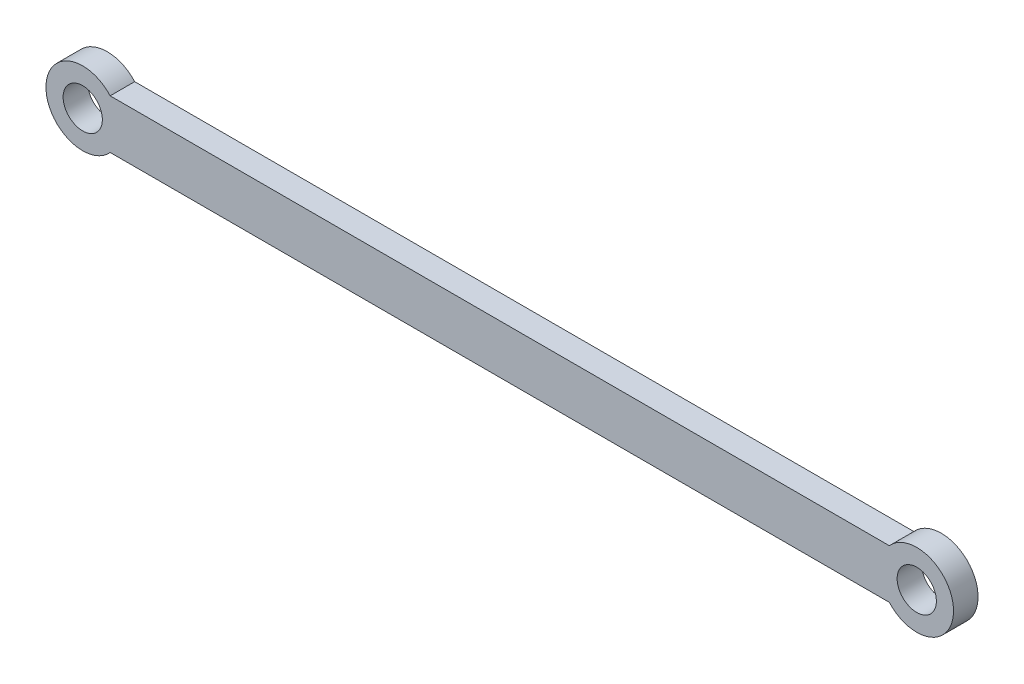
SolidWorks part; units mm, degrees
ref_plane "Piano frontale" through (0, 0, 0) normal (0, 0, 1) x (1, 0, 0)
ref_plane "Piano superiore" through (0, 0, 0) normal (0, 1, 0) x (1, 0, 0)
ref_plane "Piano destro" through (0, 0, 0) normal (1, 0, 0) x (0, 0, -1)
sketch "Schizzo1" plane through (0, 0, 0) normal (0, 0, 1) x (1, 0, 0)
  line L0 (0, 0) -> (4, 0) construction
  line L1 (5.5902, -5) -> (164.4098, -5)
  line L2 (5.5902, 5) -> (164.4098, 5)
  line L3 (0, 5) -> (170, 5) construction
  line L4 (0, -5) -> (170, -5) construction
  line L5 (166, 0) -> (170, 0) construction
  line L6 (0, 0) -> (170, 0) construction
  circle A0 centre (0, 0) radius 4
  circle A1 centre (170, 0) radius 4
  arc A2 (5.5902, 5) -> (5.5902, -5) centre (0, 0) ccw
  arc A3 (164.4098, -5) -> (164.4098, 5) centre (170, 0) ccw
  dimension "D1" = 8
  dimension "D2" = 8
  dimension "D4" = 15
  dimension "D5" = 15
  dimension "D3" = 170
  dimension "D6" = 5
  dimension "D7" = 5
extrude "Estrusione-Estrusione1" add sketch "Schizzo1" along normal blind 5
